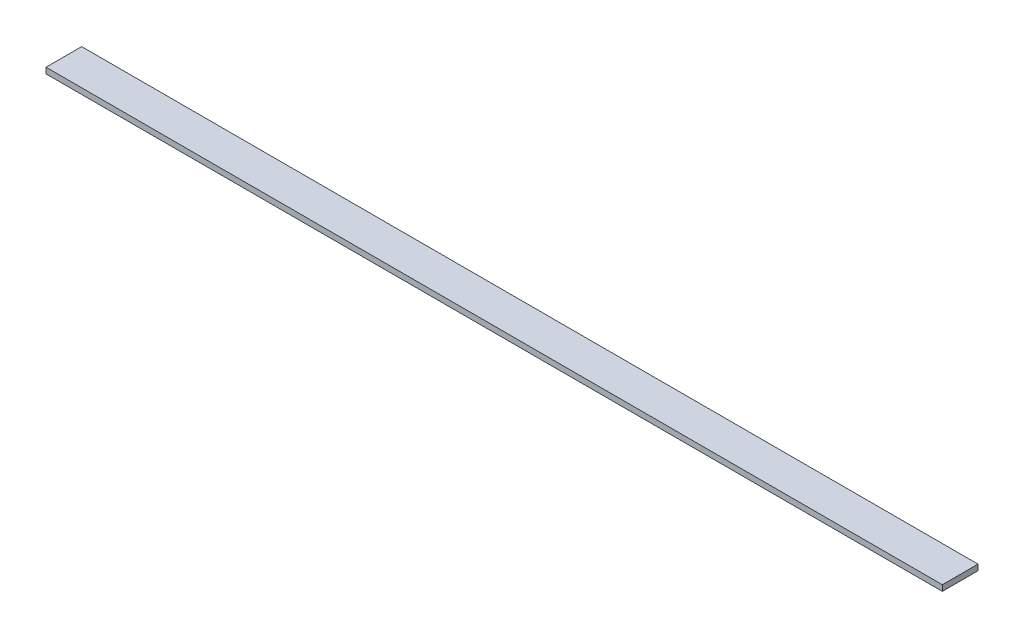
SolidWorks part; units mm, degrees
material "Pine"
ref_plane "Front Plane" through (0, 0, 0) normal (0, 0, 1) x (1, 0, 0)
ref_plane "Top Plane" through (0, 0, 0) normal (0, 1, 0) x (1, 0, 0)
ref_plane "Right Plane" through (0, 0, 0) normal (1, 0, 0) x (0, 0, -1)
sketch "Sketch3" plane through (0, 0, 0) normal (0, 1, 0) x (1, 0, 0)
  line L1 (-3811.4111, 1664.2292) -> (2094.0889, 1664.2292)
  line L2 (-3811.4111, 1664.2292) -> (-3811.4111, 1429.2792)
  line L3 (-3811.4111, 1429.2792) -> (2094.0889, 1429.2792)
  line L4 (2094.0889, 1664.2292) -> (2094.0889, 1429.2792)
  dimension "D1" = 234.95
  dimension "D2" = 5905.5
extrude "Boss-Extrude1" add sketch "Sketch3" along normal blind 38.1
